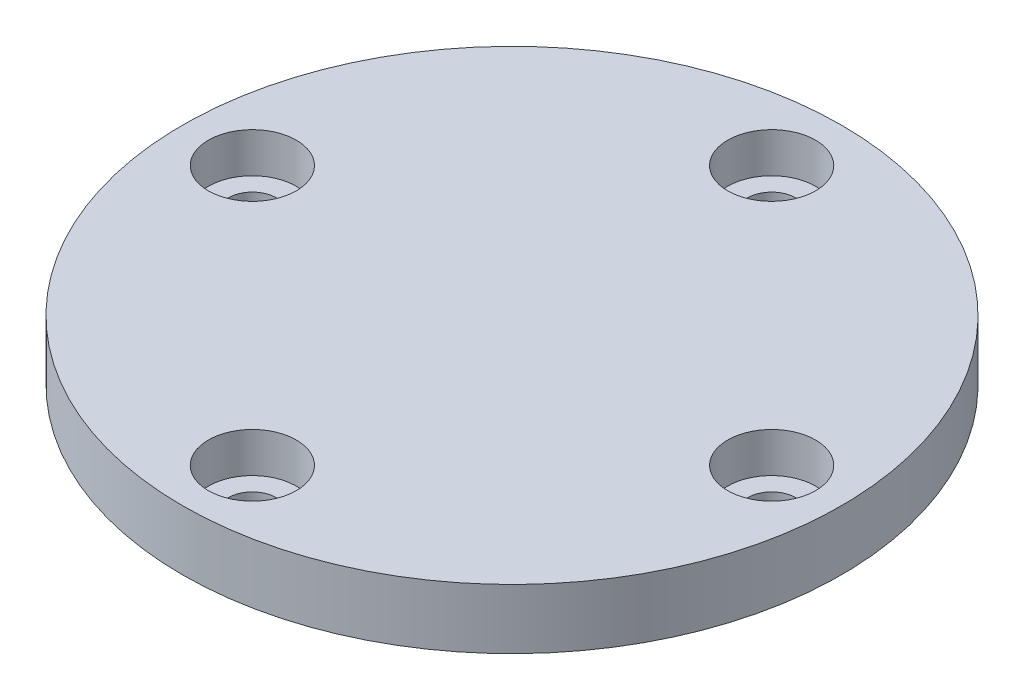
SolidWorks part; units mm, degrees
material "6061-T6 (SS)"
ref_plane "Front Plane" through (0, 0, 0) normal (0, 0, 1) x (1, 0, 0)
ref_plane "Top Plane" through (0, 0, 0) normal (0, 1, 0) x (1, 0, 0)
ref_plane "Right Plane" through (0, 0, 0) normal (1, 0, 0) x (0, 0, -1)
sketch "Sketch1" plane through (0, 0, 0) normal (0, 1, 0) x (1, 0, 0)
  circle A0 centre (0, 0) radius 16.5
  dimension "D1" = 33
extrude "Boss-Extrude1" add sketch "Sketch1" along normal blind 3
sketch "Sketch7" plane through (0, 3, 0) normal (0, 1, 0) x (1, 0, 0)
  circle A0 centre (0, -10.25) radius 0.25
  circle A1 centre (0, 0) radius 9.8
  dimension "D1" = 0.5
  dimension "D2" = 10.25
  dimension "D3" = 19.6
sketch "Sketch8" plane through (0, 3, 0) normal (0, 1, 0) x (1, 0, 0)
  line L0 (0, 0) -> (13.2071, 13.2071) construction
  circle A0 centre (7.7782, 7.7782) radius 1
  dimension "D1" = 2
  dimension "D2" = 11
sketch "Sketch9" plane through (0, 3, 0) normal (0, 1, 0) x (1, 0, 0)
  circle A0 centre (0, 0) radius 11
  dimension "D1" = 22
hole_wizard "CBORE for M2 SHCS1" positions "Sketch13" profile "Sketch14" counterbore size "M2" standard "ANSI Metric" end condition through all
sketch "Sketch13" plane through (0, 3, 0) normal (0, 1, 0) x (1, 0, 0)
  circle A0 centre (0, 0) radius 11 construction
  point P0 (-13, 0)
  dimension "D1" = 13
sketch "Sketch14" plane through (-13, 3, 0) normal (1, 0, 0) x (0, 0, 1)
  line L0 (0, 0) -> (0, 3)
  line L1 (0, 3) -> (1.2, 3)
  line L3 (1.2, 3) -> (1.2, 2)
  line L4 (1.2, 2) -> (2.2, 2)
  line L5 (2.2, 2) -> (2.2, 0)
  line L7 (2.2, 0) -> (0, 0)
  line L11 (0, -6.35) -> (0, 107.95) construction
  dimension "Thru Hole Dia." = 2.4
  dimension "Thru Hole Depth" = 3
  dimension "C'Bore Dia." = 4.4
  dimension "C'Bore Depth" = 2
pattern_circular "CirPattern1" count 4 over 360 about axis through (0, 0, 0) along (0, 1, 0) of "CBORE for M2 SHCS1"
